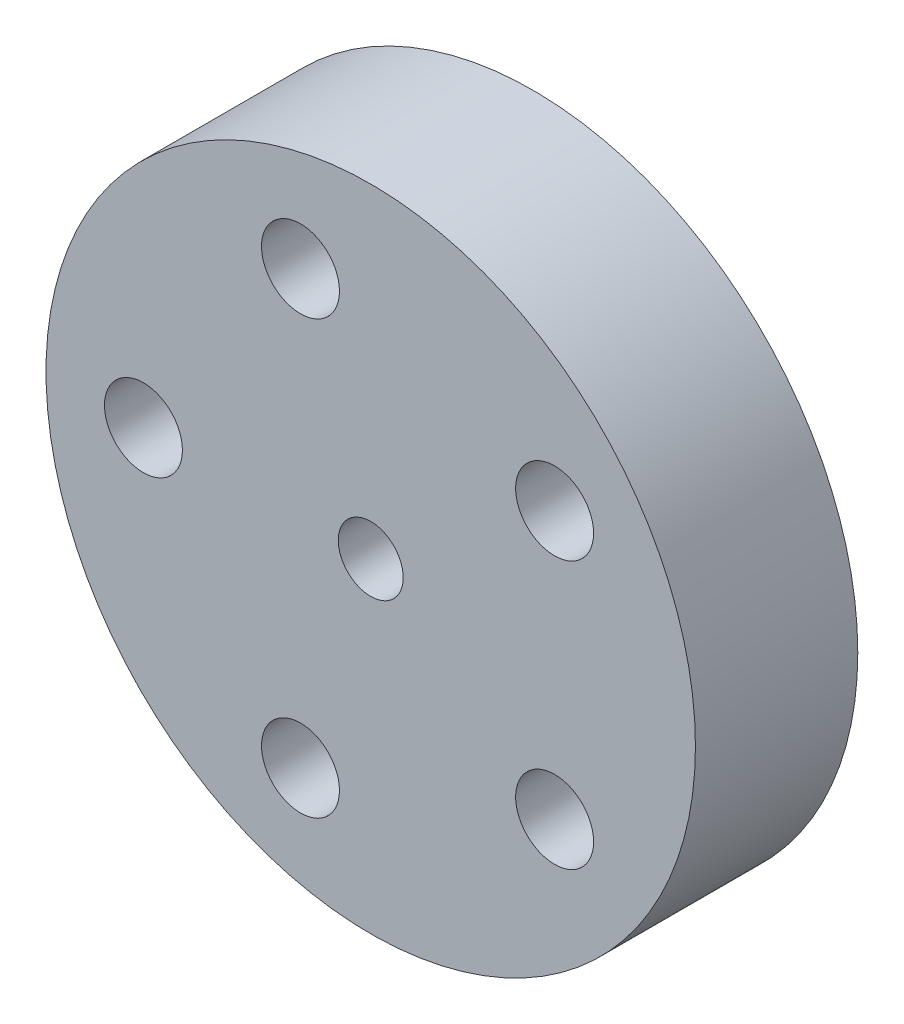
SolidWorks part; units mm, degrees
ref_plane "Front Plane" through (0, 0, 0) normal (0, 0, 1) x (1, 0, 0)
ref_plane "Top Plane" through (0, 0, 0) normal (0, 1, 0) x (1, 0, 0)
ref_plane "Right Plane" through (0, 0, 0) normal (1, 0, 0) x (0, 0, -1)
sketch "Sketch1" plane through (0, 0, 0) normal (0, 0, 1) x (1, 0, 0)
  circle A0 centre (0, 0) radius 0.635
  circle A1 centre (0, 0) radius 6.35
  dimension "D1" = 1.27
  dimension "D2" = 12.7
  dimension "D3" = 12.7
extrude "Boss-Extrude1" add sketch "Sketch1" along normal blind 3.175
sketch "Sketch2" plane through (0, 0, 3.175) normal (0, 0, 1) x (1, 0, 0)
  circle A1 centre (-4.445, 0) radius 0.762
  circle A2 centre (-1.3736, 4.2274) radius 0.762
  circle A3 centre (3.5961, 2.6127) radius 0.762
  circle A4 centre (3.5961, -2.6127) radius 0.762
  circle A5 centre (-1.3736, -4.2274) radius 0.762
  point P15 (0, 0)
  dimension "D2" = 1.524
  dimension "D3" = 5
extrude "Cut-Extrude1" cut sketch "Sketch2" against normal through all
